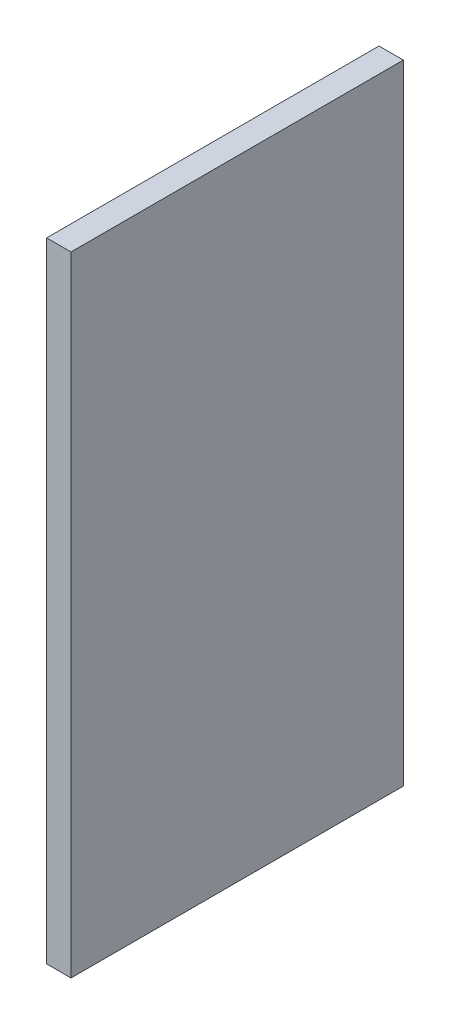
SolidWorks part; units mm, degrees
ref_plane "Front Plane" through (0, 0, 0) normal (0, 0, 1) x (1, 0, 0)
ref_plane "Top Plane" through (0, 0, 0) normal (0, 1, 0) x (1, 0, 0)
ref_plane "Right Plane" through (0, 0, 0) normal (1, 0, 0) x (0, 0, -1)
other "Configuration Table"
sketch "Sketch1" plane through (0, 0, 0) normal (0, 0, 1) x (1, 0, 0)
  line L1 (1.5, 121.5) -> (61.5, 121.5)
  line L2 (1.5, 121.5) -> (1.5, 1670)
  line L3 (1.5, 1670) -> (61.5, 1670)
  line L4 (61.5, 121.5) -> (61.5, 1670)
extrude "STORE_pu_yan_sol_1" add sketch "Sketch1" against normal blind 818.5 separate body
